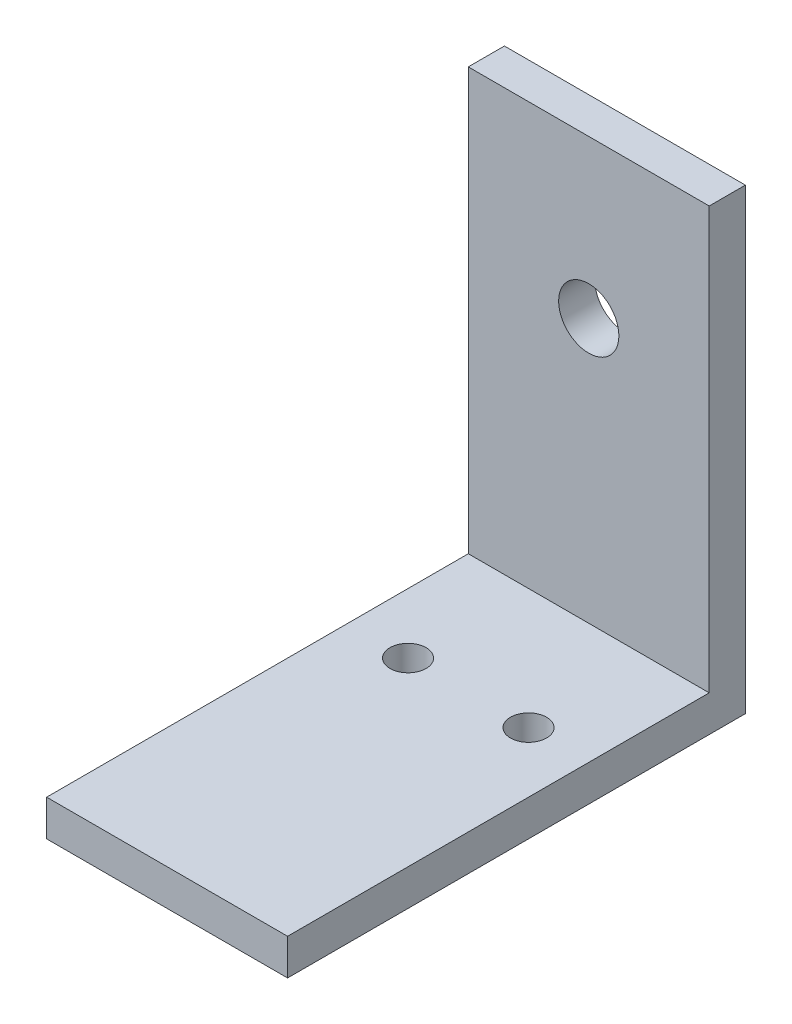
SolidWorks part; units mm, degrees
ref_plane "前视基准面" through (0, 0, 0) normal (0, 0, 1) x (1, 0, 0)
ref_plane "上视基准面" through (0, 0, 0) normal (0, 1, 0) x (1, 0, 0)
ref_plane "右视基准面" through (0, 0, 0) normal (1, 0, 0) x (0, 0, -1)
sketch "草图1" plane through (0, 0, 0) normal (0, 0, 1) x (1, 0, 0)
  line L1 (-10, 19) -> (10, 19)
  line L2 (-10, 19) -> (-10, -19)
  line L3 (-10, -19) -> (10, -19)
  line L4 (10, 19) -> (10, -19)
  line L5 (-10, 19) -> (10, -19) construction
  line L6 (-10, -19) -> (10, 19) construction
  point P0 (0, 0)
  dimension "D1" = 20
  dimension "D2" = 38
extrude "凸台-拉伸1" add sketch "草图1" along normal blind 3
sketch "草图2" plane through (0, 0, 3) normal (0, 0, 1) x (1, 0, 0)
  line L0 (10, -19) -> (10, 19) construction
  line L1 (-10, -19) -> (10, -19)
  line L2 (-10, -19) -> (-10, -16)
  line L3 (-10, -16) -> (10, -16)
  line L4 (10, -19) -> (10, -16)
  dimension "D1" = 3
extrude "凸台-拉伸2" add sketch "草图2" along normal blind 35
sketch "草图3" plane through (0, 0, 0) normal (0, 0, -1) x (-1, 0, 0)
  circle A0 centre (0, 5.916) radius 2.5
  dimension "D1" = 5
extrude "切除-拉伸1" cut sketch "草图3" against normal blind 10
sketch "草图4" plane through (0, -16, 0) normal (0, 1, 0) x (1, 0, 0)
  line L0 (-10, -38) -> (-10, -3) construction
  line L1 (10, -38) -> (10, -3) construction
  line L2 (10, -38) -> (-10, -38) construction
  circle A0 centre (-5, -13) radius 1.5
  circle A1 centre (5, -13) radius 1.5
  dimension "D1" = 5
  dimension "D2" = 5
  dimension "D3" = 3
  dimension "D4" = 3
  dimension "D5" = 25
  dimension "D6" = 25
extrude "切除-拉伸2" cut sketch "草图4" against normal blind 10
